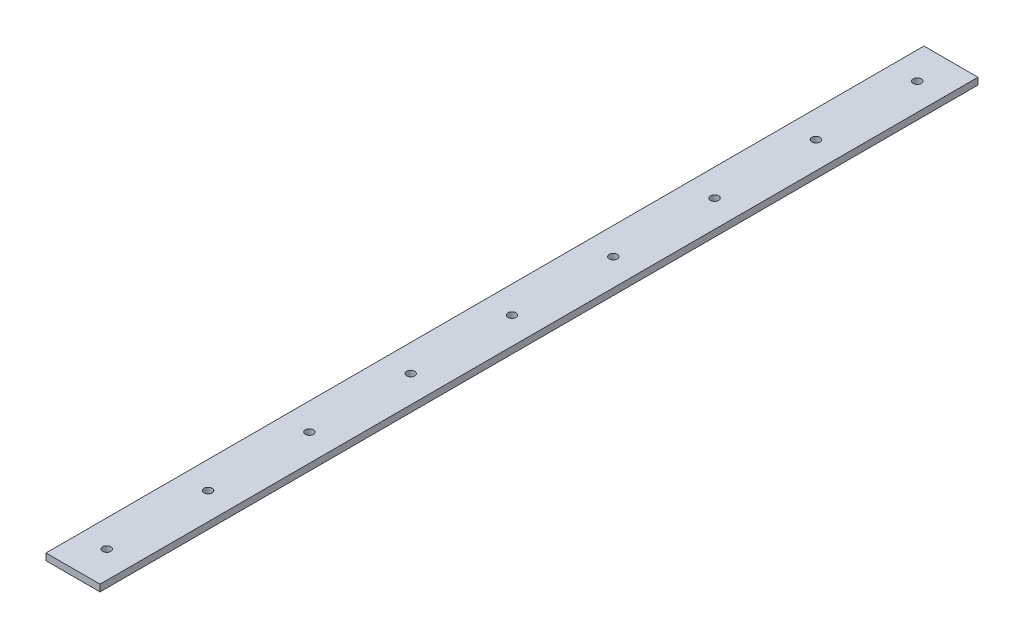
SolidWorks part; units mm, degrees
ref_plane "Front Plane" through (0, 0, 0) normal (0, 0, 1) x (1, 0, 0)
ref_plane "Top Plane" through (0, 0, 0) normal (0, 1, 0) x (1, 0, 0)
ref_plane "Right Plane" through (0, 0, 0) normal (1, 0, 0) x (0, 0, -1)
sketch "Sketch1" plane through (0, 0, 0) normal (0, 1, 0) x (1, 0, 0)
  line L1 (-20, -325) -> (20, -325)
  line L2 (-20, -325) -> (-20, 325)
  line L3 (-20, 325) -> (20, 325)
  line L4 (20, -325) -> (20, 325)
  line L5 (-20, -325) -> (20, 325) construction
  line L6 (-20, 325) -> (20, -325) construction
  point P0 (0, 0)
  dimension "D1" = 40
  dimension "D2" = 650
extrude "Boss-Extrude1" add sketch "Sketch1" along normal blind 5
sketch "Sketch2" plane through (0, 0, 0) normal (0, 1, 0) x (1, 0, 0)
  line L0 (-2.75, 0) -> (2.75, 0) construction
  circle A14 centre (0, 0) radius 3
  circle A15 centre (0, 75) radius 3
  circle A16 centre (0, 150) radius 3
  circle A17 centre (0, 225) radius 3
  circle A18 centre (0, 300) radius 3
  circle A19 centre (0, -300) radius 3
  circle A20 centre (0, -225) radius 3
  circle A21 centre (0, -150) radius 3
  circle A22 centre (0, -75) radius 3
  dimension "D1" = 6
extrude "Cut-Extrude1" cut sketch "Sketch2" along normal through all both and the other way through all
extrude "Cut-Extrude2" cut sketch "Sketch3" against normal blind 600
sketch "Sketch3" plane through (168.3641, -133.6674, 1001.0901) normal (-1, 0, 0) x (0, -1, 0)
  line L1 (-764.1656, -1134.4713) -> (-484.1656, -1134.4713)
  line L2 (-764.1656, -1134.4713) -> (-764.1656, -662.4713)
  line L3 (-764.1656, -662.4713) -> (-484.1656, -662.4713)
  line L4 (-484.1656, -1134.4713) -> (-484.1656, -662.4713)
  line L5 (-764.1656, -1134.4713) -> (-484.1656, -662.4713) construction
  line L6 (-764.1656, -662.4713) -> (-484.1656, -1134.4713) construction
  line L10 (-189.1656, -662.4713) -> (-79.1656, -662.4713)
  line L11 (-199.1656, -672.4713) -> (-199.1656, -1124.4713)
  line L12 (-189.1656, -1134.4713) -> (-79.1656, -1134.4713)
  line L13 (-69.1656, -672.4713) -> (-69.1656, -1124.4713)
  arc A0 (-79.1656, -662.4713) -> (-69.1656, -672.4713) centre (-79.1656, -672.4713) cw
  arc A1 (-189.1656, -662.4713) -> (-199.1656, -672.4713) centre (-189.1656, -672.4713) ccw
  arc A2 (-79.1656, -1134.4713) -> (-69.1656, -1124.4713) centre (-79.1656, -1124.4713) ccw
  arc A3 (-199.1656, -1124.4713) -> (-189.1656, -1134.4713) centre (-189.1656, -1124.4713) ccw
  point P0 (-624.1656, -898.4713)
  point P21 (-69.1656, -662.4713)
  point P24 (-199.1656, -662.4713)
  point P27 (-69.1656, -1134.4713)
